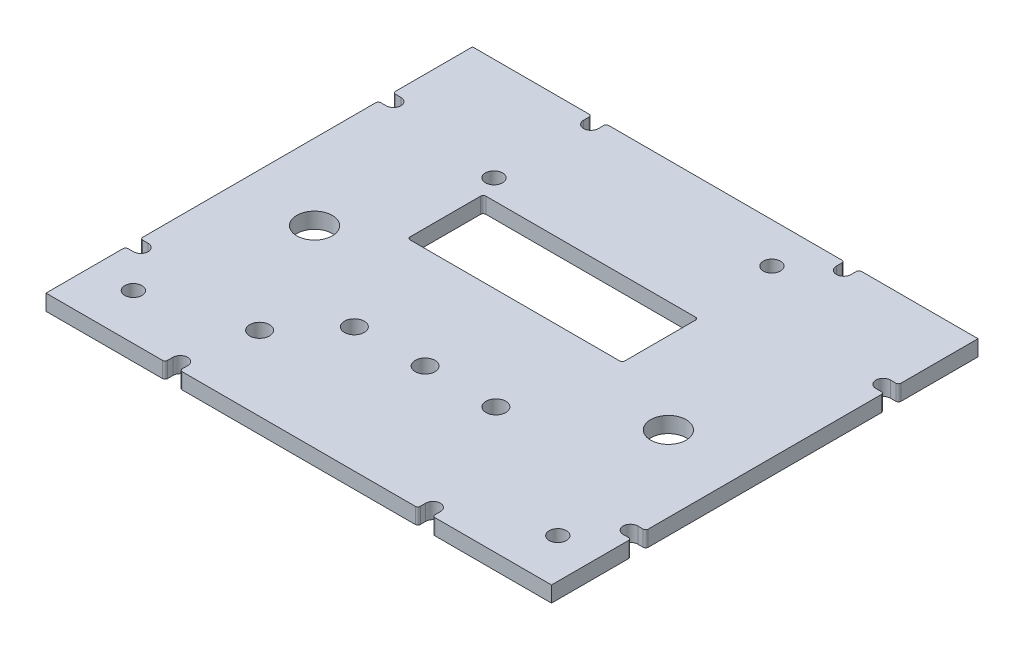
SolidWorks part; units mm, degrees
ref_plane "Front Plane" through (0, 0, 0) normal (0, 0, 1) x (1, 0, 0)
ref_plane "Top Plane" through (0, 0, 0) normal (0, 1, 0) x (1, 0, 0)
ref_plane "Right Plane" through (0, 0, 0) normal (1, 0, 0) x (0, 0, -1)
sketch "Sketch1" plane through (0, 0, 0) normal (0, 1, 0) x (1, 0, 0)
  line L1 (-50.8, -42.8625) -> (50.8, -42.8625)
  line L2 (-50.8, -42.8625) -> (-50.8, 42.8625)
  line L3 (-50.8, 42.8625) -> (50.8, 42.8625)
  line L4 (50.8, -42.8625) -> (50.8, 42.8625)
  line L5 (-50.8, -42.8625) -> (50.8, 42.8625) construction
  line L6 (-50.8, 42.8625) -> (50.8, -42.8625) construction
  point P0 (0, 0)
  dimension "D1" = 101.6
  dimension "D2" = 85.725
extrude "Boss-Extrude1" add sketch "Sketch1" along normal blind 3.175
hole_wizard "#29 (0.136) Diameter Hole1" positions "Sketch2" profile "Sketch3" hole size "#29" standard "ANSI Inch" end condition through all
sketch "Sketch2" plane through (0, 3.175, 0) normal (0, 1, 0) x (1, 0, 0)
  point P0 (-25.8318, 22.2123)
  point P3 (17.4498, 34.7853)
  point P6 (42.8498, -33.6423)
  point P9 (-42.4688, -33.6423)
sketch "Sketch3" plane through (-25.8318, 3.175, -22.2123) normal (1, 0, 0) x (0, 0, 1)
  line L0 (0, 0) -> (0, 3.175)
  line L1 (0, 3.175) -> (1.7272, 3.175)
  line L2 (1.7272, 3.175) -> (1.7272, 0)
  line L5 (1.7272, 0) -> (0, 0)
  line L11 (0, -6.35) -> (0, 107.95) construction
  dimension "Thru Hole Dia." = 3.4544
  dimension "Thru Hole Depth" = 3.175
hole_wizard "9/32 (0.28125) Diameter Hole1" positions "Sketch4" profile "Sketch5" hole size "9/32" standard "ANSI Inch" end condition through all
sketch "Sketch4" plane through (0, 3.175, 0) normal (0, 1, 0) x (1, 0, 0)
  point P0 (-35.56, -4.1275)
  point P3 (35.56, -4.1275)
sketch "Sketch5" plane through (-35.56, 3.175, 4.1275) normal (1, 0, 0) x (0, 0, 1)
  line L0 (0, 0) -> (0, 3.175)
  line L1 (0, 3.175) -> (3.5719, 3.175)
  line L2 (3.5719, 3.175) -> (3.5719, 0)
  line L5 (3.5719, 0) -> (0, 0)
  line L11 (0, -6.35) -> (0, 107.95) construction
  dimension "Thru Hole Dia." = 7.1437
  dimension "Thru Hole Depth" = 3.175
hole_wizard "5/32 (0.15625) Diameter Hole1" positions "Sketch6" profile "Sketch7" hole size "5/32" standard "ANSI Inch" end condition through all
sketch "Sketch6" plane through (0, 3.175, 0) normal (0, 1, 0) x (1, 0, 0)
  point P0 (-22.86, -27.8765)
  point P3 (-13.9422, -17.7443)
  point P6 (0, -17.4625)
  point P9 (14.224, -17.4625)
sketch "Sketch7" plane through (-22.86, 3.175, 27.8765) normal (1, 0, 0) x (0, 0, 1)
  line L0 (0, 0) -> (0, 3.175)
  line L1 (0, 3.175) -> (1.9844, 3.175)
  line L2 (1.9844, 3.175) -> (1.9844, 0)
  line L5 (1.9844, 0) -> (0, 0)
  line L11 (0, -6.35) -> (0, 107.95) construction
  dimension "Thru Hole Dia." = 3.9688
  dimension "Thru Hole Depth" = 3.175
sketch "Sketch8" plane through (0, 3.175, 0) normal (0, 1, 0) x (1, 0, 0)
  line L0 (-24.003, 18.2245) -> (19.177, 18.2245)
  line L5 (19.177, 18.2245) -> (19.177, 2.9845)
  line L6 (-24.003, 2.9845) -> (19.177, 2.9845)
  line L7 (-24.003, 18.2245) -> (-24.003, 2.9845)
  circle A0 centre (-25.8318, 22.2123) radius 1.7272 construction
  dimension "D1" = 1.8288
  dimension "D2" = 45.0088
  dimension "D3" = 3.9878
  dimension "D4" = 19.2278
extrude "Cut-Extrude1" cut sketch "Sketch8" against normal through all
sketch "Sketch9" plane through (0, 3.175, 0) normal (0, 1, 0) x (1, 0, 0)
  line L0 (-50.8, 42.8625) -> (50.8, -42.8625) construction
  line L1 (50.8, 42.8625) -> (-50.8, 42.8625) construction
  line L2 (49.2125, -41.275) -> (-49.2125, -41.275) construction
  line L3 (49.2125, -41.275) -> (49.2125, 41.275) construction
  line L4 (49.2125, 41.275) -> (-49.2125, 41.275) construction
  line L5 (-49.2125, -41.275) -> (-49.2125, 41.275) construction
  line L6 (49.2125, -41.275) -> (-49.2125, 41.275) construction
  line L7 (49.2125, 41.275) -> (-49.2125, -41.275) construction
  line L8 (-50.8, 42.8625) -> (-50.8, -42.8625) construction
  line L9 (-49.2125, 26.8732) -> (-50.8, 26.8732)
  line L10 (-49.2125, 23.9268) -> (-50.8, 23.9268)
  line L11 (-50.8, 26.8732) -> (-50.8, 23.9268)
  line L12 (-49.2125, -23.9268) -> (-50.8, -23.9268)
  line L13 (-50.8, -23.9268) -> (-50.8, -26.8732)
  line L14 (-49.2125, -26.8732) -> (-50.8, -26.8732)
  line L15 (0, 0) -> (0, 12.7264) construction
  line L16 (49.2125, -26.8732) -> (50.8, -26.8732)
  line L17 (50.8, -23.9268) -> (50.8, -26.8732)
  line L18 (49.2125, -23.9268) -> (50.8, -23.9268)
  line L19 (50.8, 26.8732) -> (50.8, 23.9268)
  line L20 (49.2125, 23.9268) -> (50.8, 23.9268)
  line L21 (49.2125, 26.8732) -> (50.8, 26.8732)
  line L23 (-24.003, 2.9845) -> (19.177, 2.9845) construction
  arc A0 (-49.2125, 23.9268) -> (-49.2125, 26.8732) centre (-49.2125, 25.4) ccw
  arc A1 (-49.2125, -26.8732) -> (-49.2125, -23.9268) centre (-49.2125, -25.4) ccw
  arc A2 (49.2125, -26.8732) -> (49.2125, -23.9268) centre (49.2125, -25.4) cw
  arc A3 (49.2125, 23.9268) -> (49.2125, 26.8732) centre (49.2125, 25.4) cw
  point P4 (0, 0)
  point P16 (-49.2125, 0)
  dimension "D3" = 25.4
  dimension "D5" = 1.4732
  dimension "D1" = 1.5875
  dimension "D2" = 1.5875
  dimension "D6" = 28.3845
  dimension "D4" = 2
extrude "Cut-Extrude2" cut sketch "Sketch9" against normal through all
fillet "Fillet1" radius 0.508 12 edges at (50.8, 1.5875, -23.9268) (50.8, 1.5875, -26.8732) (50.8, 1.5875, 23.9268) (50.8, 1.5875, 26.8732) (-50.8, 1.5875, 23.9268) (-50.8, 1.5875, 26.8732) (-50.8, 1.5875, -23.9268) (-50.8, 1.5875, -26.8732) (-24.003, 1.5875, -2.9845) (19.177, 1.5875, -2.9845) (19.177, 1.5875, -18.2245) (-24.003, 1.5875, -18.2245)
sketch "Sketch10" plane through (0, 3.175, 0) normal (0, 1, 0) x (1, 0, 0)
  line L0 (-50.8, -42.8625) -> (50.8, -42.8625) construction
  line L1 (49.2125, 41.275) -> (-49.2125, 41.275) construction
  line L2 (49.2125, 41.275) -> (49.2125, -41.275) construction
  line L3 (49.2125, -41.275) -> (26.8732, -41.275) construction
  line L4 (-49.2125, 41.275) -> (-49.2125, -41.275) construction
  line L5 (49.2125, 41.275) -> (-49.2125, -41.275) construction
  line L6 (49.2125, -41.275) -> (-49.2125, 41.275) construction
  line L7 (50.8, -23.4188) -> (50.8, 23.4188) construction
  line L8 (0, 0) -> (-50.8, 0) construction
  line L9 (-50.8, 23.4188) -> (-50.8, -23.4188) construction
  line L10 (0, 0) -> (0, -42.8625) construction
  line L11 (-26.8732, -41.275) -> (-49.2125, -41.275) construction
  line L12 (-23.9268, 41.275) -> (-23.9268, 42.8625)
  line L13 (26.8732, -41.275) -> (26.8732, -42.8625)
  line L14 (26.8732, -42.8625) -> (23.9268, -42.8625)
  line L15 (23.9268, -41.275) -> (23.9268, -42.8625)
  line L16 (23.9268, -41.275) -> (-23.9268, -41.275) construction
  line L17 (-23.9268, -41.275) -> (-23.9268, -42.8625)
  line L18 (-23.9268, -42.8625) -> (-26.8732, -42.8625)
  line L19 (-26.8732, -41.275) -> (-26.8732, -42.8625)
  line L20 (-23.9268, 42.8625) -> (-26.8732, 42.8625)
  line L21 (-26.8732, 41.275) -> (-26.8732, 42.8625)
  line L22 (26.8732, 42.8625) -> (23.9268, 42.8625)
  line L23 (26.8732, 41.275) -> (26.8732, 42.8625)
  line L24 (23.9268, 41.275) -> (23.9268, 42.8625)
  arc A0 (26.8732, -41.275) -> (23.9268, -41.275) centre (25.4, -41.275) ccw
  arc A1 (-23.9268, -41.275) -> (-26.8732, -41.275) centre (-25.4, -41.275) ccw
  arc A2 (-23.9268, 41.275) -> (-26.8732, 41.275) centre (-25.4, 41.275) cw
  arc A3 (26.8732, 41.275) -> (23.9268, 41.275) centre (25.4, 41.275) cw
  point P0 (0, 0)
  dimension "D3" = 2.9464
  dimension "D4" = 25.4
  dimension "D5" = 25.4
  dimension "D1" = 1.5875
  dimension "D2" = 1.5875
extrude "Cut-Extrude3" cut sketch "Sketch10" against normal through all
fillet "Fillet2" radius 0.508 8 edges at (26.8732, 1.5875, -42.8625) (23.9268, 1.5875, -42.8625) (-26.8732, 1.5875, -42.8625) (-23.9268, 1.5875, -42.8625) (-23.9268, 1.5875, 42.8625) (-26.8732, 1.5875, 42.8625) (23.9268, 1.5875, 42.8625) (26.8732, 1.5875, 42.8625)
